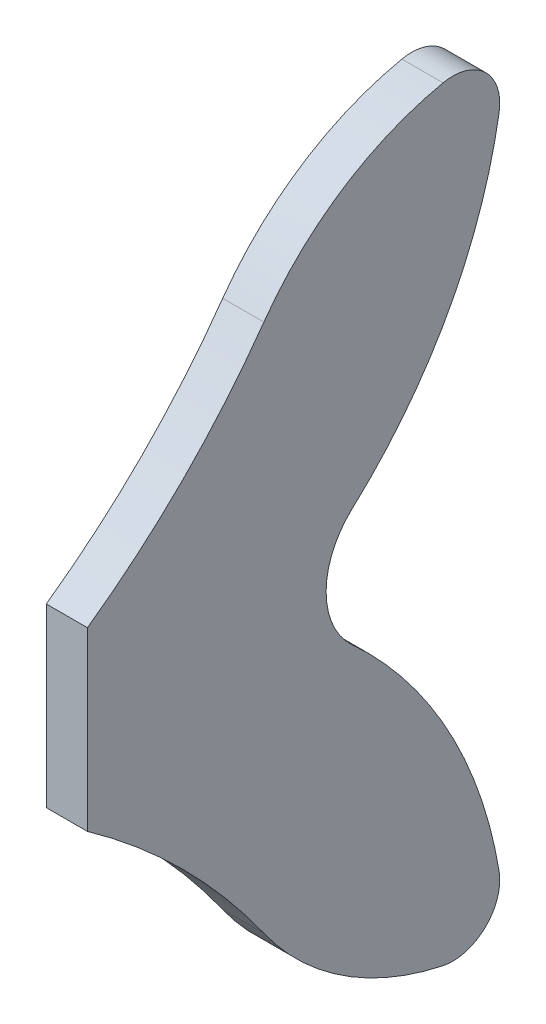
SolidWorks part; units mm, degrees
ref_plane "Front Plane" through (0, 0, 0) normal (0, 0, 1) x (1, 0, 0)
ref_plane "Top Plane" through (0, 0, 0) normal (0, 1, 0) x (1, 0, 0)
ref_plane "Right Plane" through (0, 0, 0) normal (1, 0, 0) x (0, 0, -1)
sketch "Sketch1" plane through (0, 0, 0) normal (1, 0, 0) x (0, 0, -1)
  line L0 (0, 15) -> (0, -15)
  line L1 (55, 0) -> (-55, 0) construction
  arc A0 (0, 15) -> (30, 45) centre (-73.1287, 118.1287) ccw
  arc A1 (30, 45) -> (60.4586, 65) centre (70.7864, 16.0783) cw
  arc A2 (60.4586, 65) -> (70, 55.8444) centre (62.111, 57.1725) cw
  arc A3 (70, 55.8444) -> (45, 10) centre (-8.8898, 69.1261) cw
  arc A4 (70, -55.8444) -> (45, -10) centre (-8.8898, -69.1261) ccw
  arc A5 (60.4586, -65) -> (70, -55.8444) centre (62.111, -57.1725) ccw
  arc A6 (30, -45) -> (60.4586, -65) centre (70.7864, -16.0783) ccw
  arc A7 (0, -15) -> (30, -45) centre (-73.1287, -118.1287) cw
  arc A8 (45, 10) -> (45, -10) centre (54.1144, 0) ccw
  point P18 (0, 0)
  dimension "D2" = 30
  dimension "D3" = 50
  dimension "D4" = 8
  dimension "D5" = 80
  dimension "D1" = 10
  dimension "D6" = 45
  dimension "D7" = 70
  dimension "D8" = 15
  dimension "D9" = 65
  dimension "D10" = 30
extrude "Boss-Extrude1" add sketch "Sketch1" along normal mid plane 7
